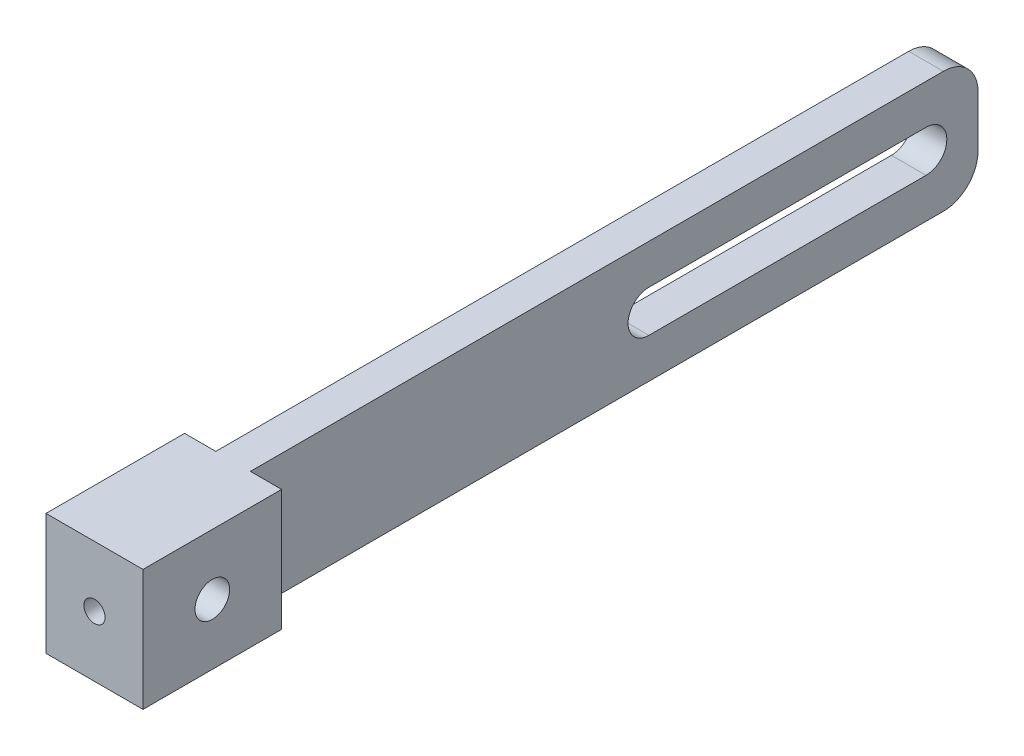
SolidWorks part; units mm, degrees
ref_plane "Front Plane" through (0, 0, 0) normal (0, 0, 1) x (1, 0, 0)
ref_plane "Top Plane" through (0, 0, 0) normal (0, 1, 0) x (1, 0, 0)
ref_plane "Right Plane" through (0, 0, 0) normal (1, 0, 0) x (0, 0, -1)
sketch "Sketch1" plane through (0, 0, 0) normal (0, 0, 1) x (1, 0, 0)
  line L1 (-14, 17.5) -> (14, 17.5)
  line L2 (-14, 17.5) -> (-14, -17.5)
  line L3 (-14, -17.5) -> (14, -17.5)
  line L4 (14, 17.5) -> (14, -17.5)
  line L5 (-14, 17.5) -> (14, -17.5) construction
  line L6 (-14, -17.5) -> (14, 17.5) construction
  circle A0 centre (0, 0) radius 3.05
  point P0 (0, 0)
  dimension "D3" = 6.1
  dimension "D1" = 28
  dimension "D2" = 35
extrude "Boss-Extrude1" add sketch "Sketch1" against normal blind 40
sketch "Sketch2" plane through (0, 0, 0) normal (1, 0, 0) x (0, 0, -1)
  line L0 (40, -17.5) -> (40, 17.5) construction
  circle A0 centre (20, 0) radius 5
  point P4 (0, 0)
  point P5 (40, 0)
  dimension "D1" = 10
  dimension "D2" = 20
extrude "Cut-Extrude1" cut sketch "Sketch2" against normal through all both and the other way through all
sketch "Sketch4" plane through (0, 0, 0) normal (1, 0, 0) x (0, 0, -1)
  line L0 (40, -17.5) -> (0, -17.5) construction
  line L1 (40, 17.5) -> (250, 17.5)
  line L2 (40, 17.5) -> (40, -17.5)
  line L3 (40, -17.5) -> (250, -17.5)
  line L4 (250, 17.5) -> (250, -17.5)
  line L5 (0, -17.5) -> (0, 17.5) construction
  line L6 (235, 0) -> (155, 0) construction
  line L7 (235, -6) -> (155, -6)
  line L8 (235, 6) -> (155, 6)
  arc A0 (235, -6) -> (235, 6) centre (235, 0) ccw
  arc A1 (155, 6) -> (155, -6) centre (155, 0) ccw
  point P12 (195, 0)
  point P17 (185.8209, 0)
  dimension "D1" = 250
  dimension "D2" = 12
  dimension "D3" = 80
  dimension "D4" = 15
extrude "Boss-Extrude2" add sketch "Sketch4" along normal blind 5 and the other way blind 5
fillet "Fillet1" radius 10 2 edges at (0, -17.5, -250) (0, 17.5, -250)
